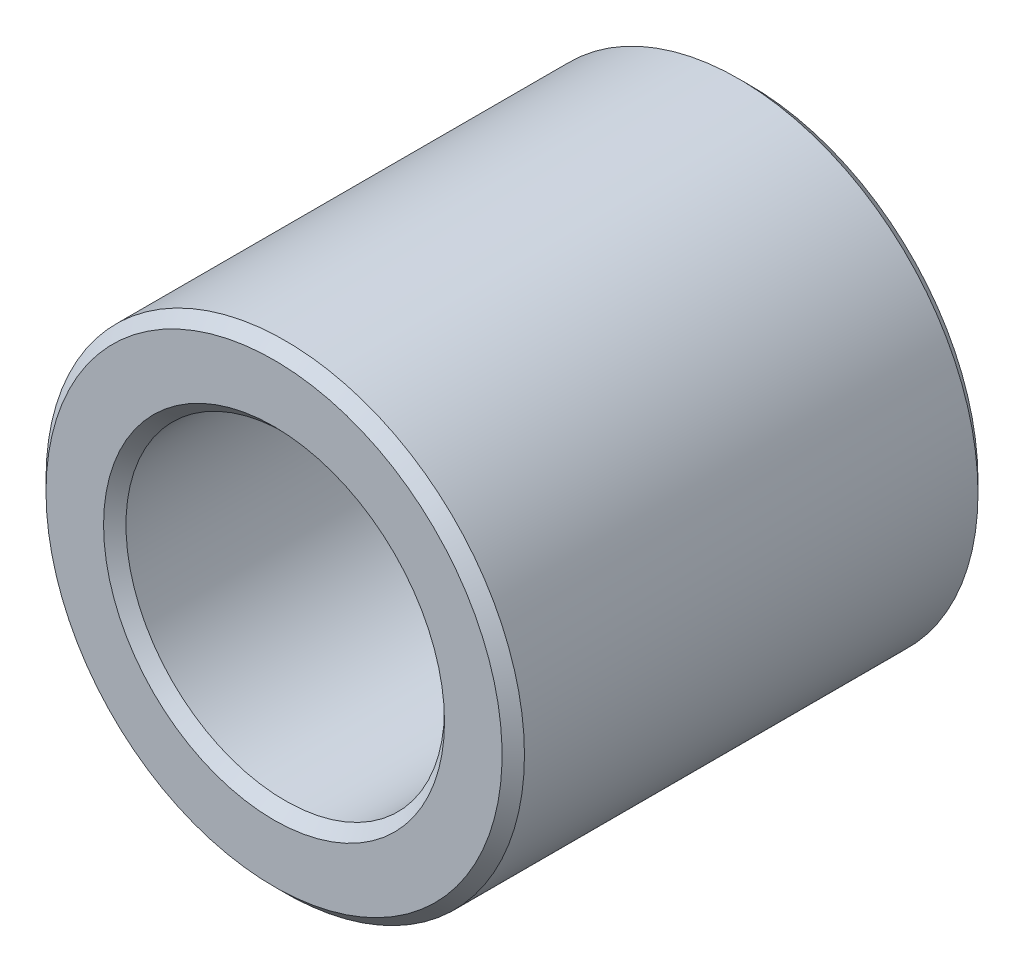
SolidWorks part; units mm, degrees
ref_plane "Front Plane" through (0, 0, 0) normal (0, 0, 1) x (1, 0, 0)
ref_plane "Top Plane" through (0, 0, 0) normal (0, 1, 0) x (1, 0, 0)
ref_plane "Right Plane" through (0, 0, 0) normal (1, 0, 0) x (0, 0, -1)
sketch "Sketch1" plane through (0, 0, 0) normal (0, 0, 1) x (1, 0, 0)
  line L0 (3.1877, 0) -> (4.7879, 0) construction
  circle A0 centre (0, 0) radius 3.1877 construction
  circle A1 centre (0, 0) radius 4.7879 construction
  circle A2 centre (0, 0) radius 4.7625 construction
  circle A3 centre (0, 0) radius 3.175 construction
  dimension "For Shaft Diameter" = 6.35
  dimension "For Housing ID" = 9.525
  dimension "OD" = 9.5758
  dimension "ID" = 6.3754
  dimension "D3" = 1.6002
sketch "Sketch13" plane through (0, 0, 0) normal (1, 0, 0) x (0, 0, -1)
  line L0 (4.7625, 0) -> (-4.7625, 0) construction
  line L1 (4.7625, 4.7879) -> (-4.7625, 4.7879) construction
  line L2 (0, 4.7879) -> (0, -4.7879) construction
  line L3 (0, 4.7879) -> (0, -4.7879) construction
  point P4 (0, 0)
  point P8 (0, 4.7879)
  dimension "Length" = 9.525
sketch "Sketch14" plane through (0, 0, 0) normal (0, 0, 1) x (1, 0, 0)
  circle A0 centre (0, 0) radius 3.1877 construction
  circle A1 centre (0, 0) radius 4.7879 construction
  circle A2 centre (0, 0) radius 3.1877
  circle A3 centre (0, 0) radius 4.7879
extrude "Boss-Extrude1" add sketch "Sketch14" against normal up to vertex (4.7625 mm away) and the other way up to vertex (4.7625 mm away) up to point (0, 4.7879, -4.7625) other way up to point (0, 4.7879, 4.7625)
chamfer "Chamfer1" distance 0.224 angle 45 4 edges at (4.7879, 0, -4.7625) (3.1877, 0, -4.7625) (3.1877, 0, 4.7625) (4.7879, 0, 4.7625)
equation "\"D1@Chamfer1\"=(\"OD@Sketch1\"-\"ID@Sketch1\")*.07"
